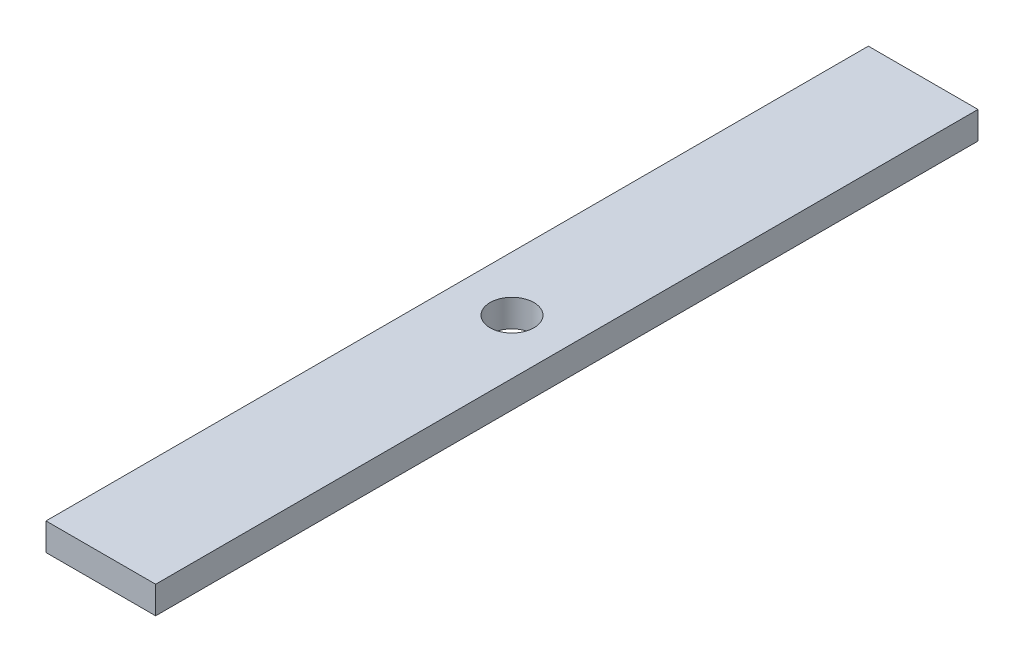
SolidWorks part; units mm, degrees
material "AISI 1045 Steel, cold drawn"
ref_plane "Front Plane" through (0, 0, 0) normal (0, 0, 1) x (1, 0, 0)
ref_plane "Top Plane" through (0, 0, 0) normal (0, 1, 0) x (1, 0, 0)
ref_plane "Right Plane" through (0, 0, 0) normal (1, 0, 0) x (0, 0, -1)
sketch "Sketch1" plane through (0, 0, 0) normal (0, 0, 1) x (1, 0, 0)
  line L1 (-10, 2.5) -> (10, 2.5)
  line L2 (-10, 2.5) -> (-10, -2.5)
  line L3 (-10, -2.5) -> (10, -2.5)
  line L4 (10, 2.5) -> (10, -2.5)
  point P4 (10, 0)
  point P6 (0, 2.5)
  dimension "D1" = 20
  dimension "D2" = 5
extrude "Boss-Extrude1" add sketch "Sketch1" along normal mid plane 212
sketch "Sketch2" plane through (0, 2.5, 0) normal (0, 1, 0) x (1, 0, 0)
  line L0 (0, 0) -> (35.2363, 0) construction
  circle A0 centre (0, 87.5) radius 4
  circle A1 centre (0, 0) radius 4
  circle A2 centre (0, -87.5) radius 4
  dimension "D1" = 8
  dimension "D2" = 175
extrude "Holes for 20mm strip ONLY" cut sketch "Sketch2" against normal through all
sketch "Sketch3" [suppressed] plane through (0, 2.5, 0) normal (0, 1, 0) x (1, 0, 0)
  line L0 (0, 0) -> (65.8821, 0) construction
  line L1 (15, -175) -> (-15, -175) construction
  circle A0 centre (0, -50) radius 2.5
  circle A1 centre (0, -150) radius 2.5
  circle A2 centre (0, 150) radius 2.5
  circle A3 centre (0, 50) radius 2.5
  point P7 (0, -175)
  dimension "D2" = 5
  dimension "D1" = 100
  dimension "D3" = 300
extrude "Cut-Extrude1" [suppressed] cut sketch "Sketch3" against normal through all
sketch "Sketch4" [suppressed] plane through (0, 2.5, 0) normal (0, 1, 0) x (1, 0, 0)
  line L0 (-10, -106) -> (-10, 106) construction
  line L1 (10, -26) -> (-10, -26)
  line L2 (10, -26) -> (10, 26)
  line L3 (10, 26) -> (-10, 26)
  line L4 (-10, -26) -> (-10, 26)
  line L5 (10, -26) -> (-10, 26) construction
  line L6 (10, 26) -> (-10, -26) construction
  point P0 (0, 0)
  dimension "D1" = 52
extrude "Cut-Extrude2" [suppressed] cut sketch "Sketch4" against normal through all flip side to cut
sketch "Sketch5" plane through (0, 2.5, 0) normal (0, 1, 0) x (1, 0, 0)
  line L1 (-25.7525, -75) -> (25.7525, -75)
  line L2 (-25.7525, -75) -> (-25.7525, 75)
  line L3 (-25.7525, 75) -> (25.7525, 75)
  line L4 (25.7525, -75) -> (25.7525, 75)
  line L5 (-25.7525, -75) -> (25.7525, 75) construction
  line L6 (-25.7525, 75) -> (25.7525, -75) construction
  point P0 (0, 0)
  dimension "D1" = 150
extrude "Cut-Extrude3" cut sketch "Sketch5" against normal through all flip side to cut
